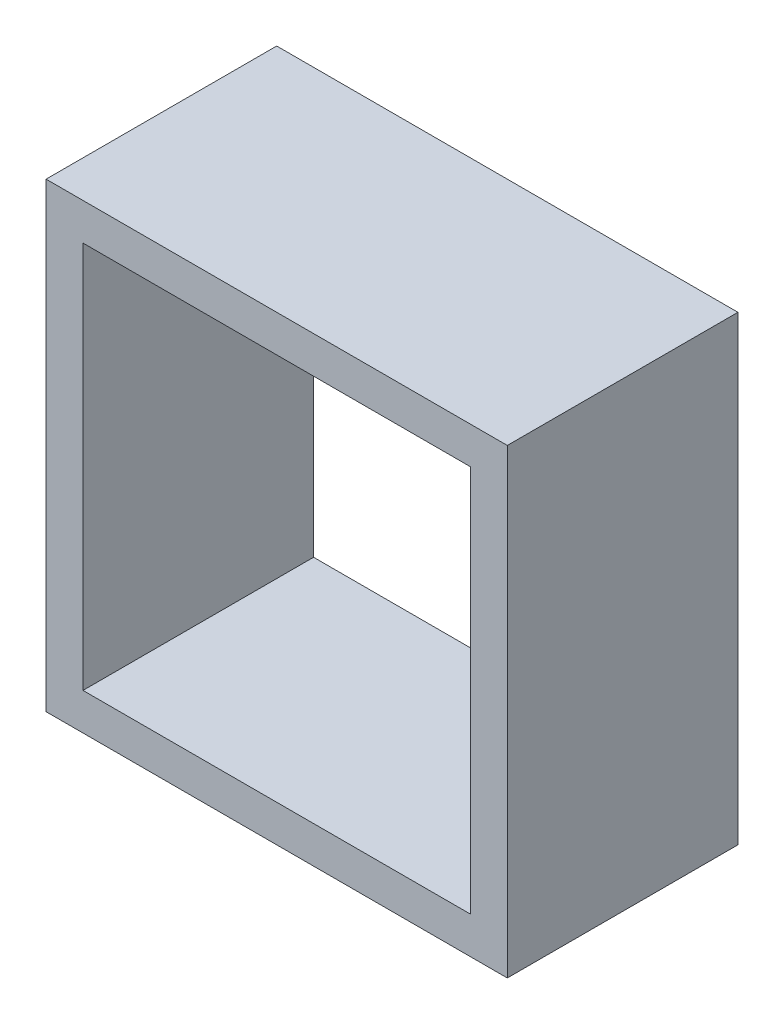
SolidWorks part; units mm, degrees
ref_plane "Plan de face" through (0, 0, 0) normal (0, 0, 1) x (1, 0, 0)
ref_plane "Plan de dessus" through (0, 0, 0) normal (0, 1, 0) x (1, 0, 0)
ref_plane "Plan de droite" through (0, 0, 0) normal (1, 0, 0) x (0, 0, -1)
sketch "Esquisse1" plane through (0, 0, 0) normal (0, 0, 1) x (1, 0, 0)
  line L0 (-4.2, 4.2) -> (4.2, 4.2)
  line L1 (-5, -5) -> (5, -5)
  line L2 (-5, -5) -> (-5, 5)
  line L3 (-5, 5) -> (5, 5)
  line L4 (5, -5) -> (5, 5)
  line L5 (-5, -5) -> (5, 5) construction
  line L6 (-5, 5) -> (5, -5) construction
  line L7 (4.2, -4.2) -> (4.2, 4.2)
  line L8 (-4.2, -4.2) -> (4.2, -4.2)
  line L9 (-4.2, -4.2) -> (-4.2, 4.2)
  point P0 (0, 0)
  dimension "D1" = 10
  dimension "D2" = 10
  dimension "D3" = 0.8
extrude "Boss.-Extru.1" add sketch "Esquisse1" along normal blind 5
